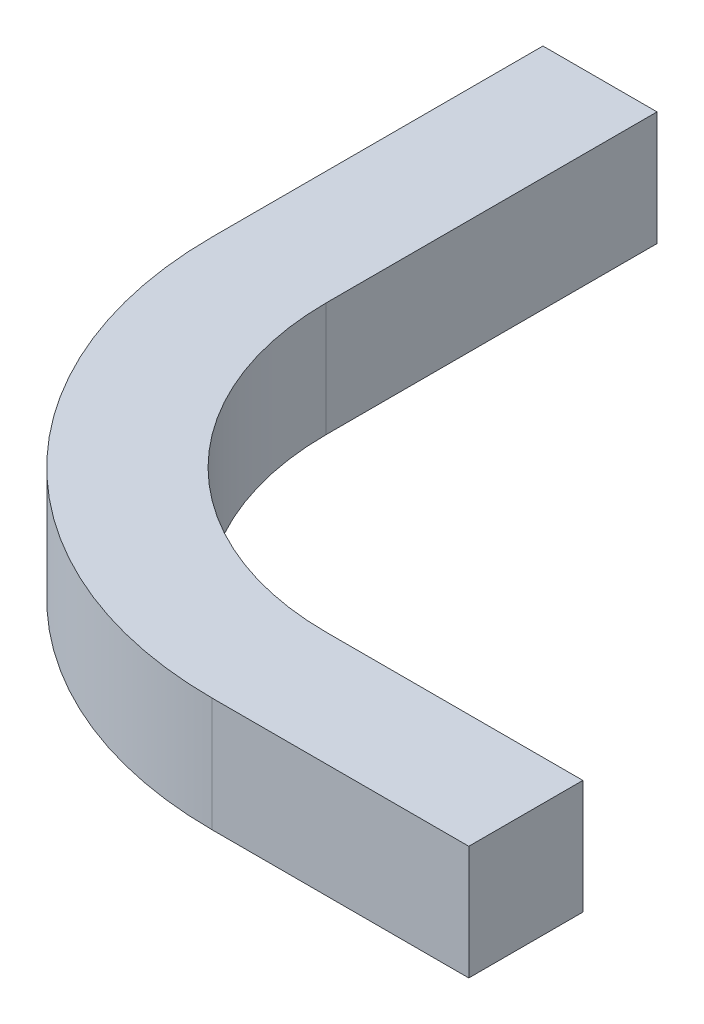
SolidWorks part; units mm, degrees
material "PTFE (general)"
ref_plane "Front Plane" through (0, 0, 0) normal (0, 0, 1) x (1, 0, 0)
ref_plane "Top Plane" through (0, 0, 0) normal (0, 1, 0) x (1, 0, 0)
ref_plane "Right Plane" through (0, 0, 0) normal (1, 0, 0) x (0, 0, -1)
sketch "Sketch1" plane through (0, 0, 0) normal (0, 1, 0) x (1, 0, 0)
  line L1 (0, 10) -> (0, -10)
  line L2 (0, -10) -> (-45, -10)
  line L4 (-115, 60) -> (-115, 118)
  line L5 (-115, 118) -> (-95, 118)
  line L6 (-95, 118) -> (-95, 60)
  line L7 (-45, 10) -> (0, 10)
  arc A0 (-115, 60) -> (-45, -10) centre (-45, 60) ccw
  arc A1 (-95, 60) -> (-45, 10) centre (-45, 60) ccw
  point P5 (0, 0)
  dimension "D5" = 115
  dimension "D1" = 50
  dimension "D3" = 70
  dimension "D2" = 20
  dimension "D4" = 20
  dimension "D6" = 128
extrude "Boss-Extrude1" add sketch "Sketch1" along normal blind 20
